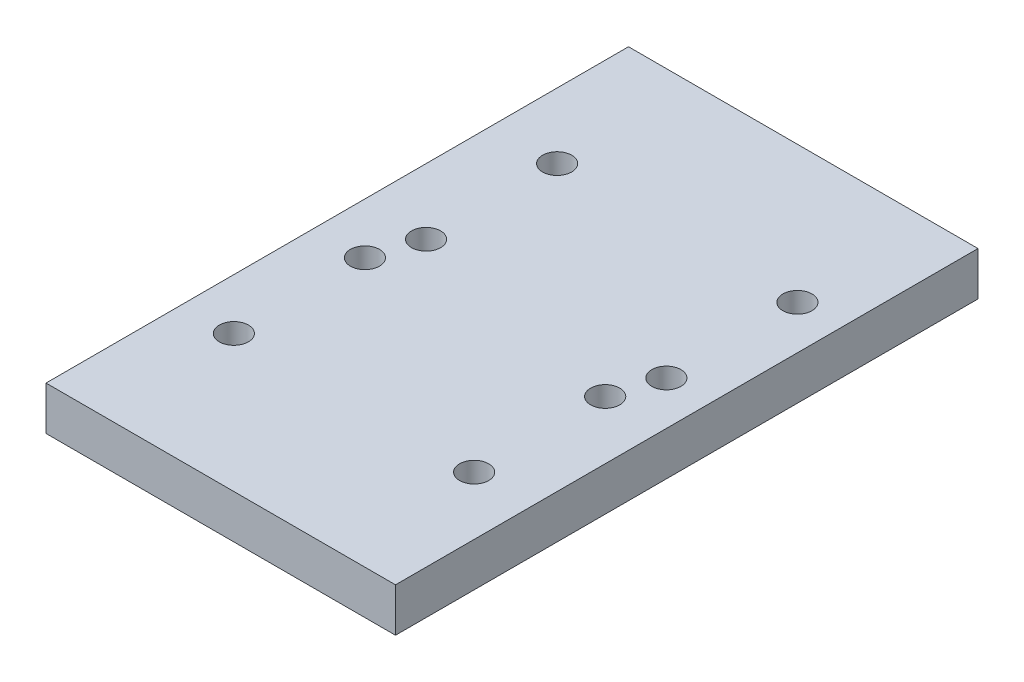
SolidWorks part; units mm, degrees
material "Aleación 6061"
ref_plane "Alzado" through (0, 0, 0) normal (0, 0, 1) x (1, 0, 0)
ref_plane "Planta" through (0, 0, 0) normal (0, 1, 0) x (1, 0, 0)
ref_plane "Vista lateral" through (0, 0, 0) normal (1, 0, 0) x (0, 0, -1)
sketch "Croquis1" plane through (0, 0, 0) normal (0, 0, 1) x (1, 0, 0)
  line L1 (-24, 3) -> (24, 3)
  line L2 (-24, 3) -> (-24, -3)
  line L3 (-24, -3) -> (24, -3)
  line L4 (24, 3) -> (24, -3)
  line L5 (-24, 3) -> (24, -3) construction
  line L6 (-24, -3) -> (24, 3) construction
  point P0 (0, 0)
  dimension "D1" = 6
  dimension "D2" = 48
extrude "Saliente-Extruir1" add sketch "Croquis1" along normal blind 80
sketch "Croquis3" plane through (0, -3, 0) normal (0, -1, 0) x (-1, 0, 0)
  line L0 (24, -80) -> (-24, -80) construction
  line L1 (-24, -80) -> (-24, 0) construction
  line L3 (24, 0) -> (-24, 0) construction
  line L4 (-18, -61.2) -> (-18, -43.2)
  line L5 (-14, -43.2) -> (-14, -61.2)
  line L6 (0.5, -71.4251) -> (0.5, -37.2376) construction
  line L7 (-20, -18.8) -> (-20, -36.8)
  line L8 (-16, -36.8) -> (-16, -18.8)
  line L9 (-1.5, -41.2964) -> (-1.5, -9.7375) construction
  line L10 (15, -43.2) -> (15, -61.2)
  line L11 (19, -61.2) -> (19, -43.2)
  line L12 (13, -36.8) -> (13, -18.8)
  line L13 (17, -18.8) -> (17, -36.8)
  arc A0 (-18, -61.2) -> (-14, -61.2) centre (-16, -61.2) ccw
  arc A1 (-16, -18.8) -> (-20, -18.8) centre (-18, -18.8) ccw
  arc A2 (-18, -43.2) -> (-14, -43.2) centre (-16, -43.2) cw
  arc A3 (-20, -36.8) -> (-16, -36.8) centre (-18, -36.8) ccw
  arc A4 (19, -43.2) -> (15, -43.2) centre (17, -43.2) ccw
  arc A5 (19, -61.2) -> (15, -61.2) centre (17, -61.2) cw
  arc A6 (17, -36.8) -> (13, -36.8) centre (15, -36.8) cw
  arc A7 (13, -18.8) -> (17, -18.8) centre (15, -18.8) cw
  dimension "D3" = 4
  dimension "D4" = 4
  dimension "D7" = 2
  dimension "D11" = 2
  dimension "D1" = 18.8
  dimension "D2" = 8
  dimension "D5" = 6
  dimension "D6" = 18.8
  dimension "D8" = 18
  dimension "D9" = 8
  dimension "D10" = 16.5
  dimension "D12" = 6
  dimension "D13" = 18
  dimension "D14" = 16.5
sketch "Croquis6" plane through (0, -3, 0) normal (0, -1, 0) x (1, 0, 0)
  circle A0 centre (16, 61.2) radius 2
  circle A1 centre (18, 36.8) radius 2
  circle A2 centre (18, 18.8) radius 2
  circle A3 centre (-17, 61.2) radius 2
  circle A4 centre (-15, 36.8) radius 2
  circle A5 centre (-15, 18.8) radius 2
  circle A6 centre (-17, 43.2) radius 2
  circle A7 centre (16, 43.2) radius 2
extrude "Cortar-Extruir4" cut sketch "Croquis6" against normal through all
